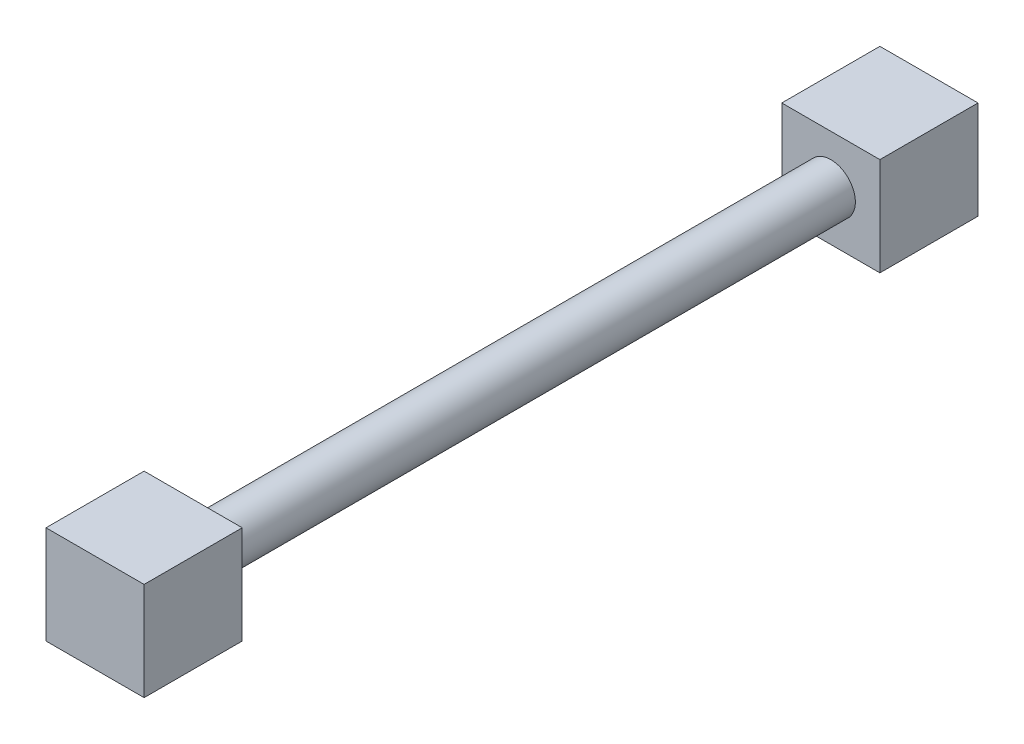
SolidWorks part; units mm, degrees
ref_plane "Front Plane" through (0, 0, 0) normal (0, 0, 1) x (1, 0, 0)
ref_plane "Top Plane" through (0, 0, 0) normal (0, 1, 0) x (1, 0, 0)
ref_plane "Right Plane" through (0, 0, 0) normal (1, 0, 0) x (0, 0, -1)
sketch "Sketch3" plane through (0, 0, 0) normal (0, 0, 1) x (1, 0, 0)
  circle A0 centre (0, 0) radius 12.7
  dimension "D1" = 25.4
extrude "Boss-Extrude1" add sketch "Sketch3" along normal blind 381
sketch "Sketch4" plane through (0, 0, 0) normal (0, 0, -1) x (-1, 0, 0)
  line L1 (-25.4, -25.4) -> (25.4, -25.4)
  line L2 (-25.4, -25.4) -> (-25.4, 25.4)
  line L3 (-25.4, 25.4) -> (25.4, 25.4)
  line L4 (25.4, -25.4) -> (25.4, 25.4)
  line L5 (-25.4, -25.4) -> (25.4, 25.4) construction
  line L6 (-25.4, 25.4) -> (25.4, -25.4) construction
  point P0 (0, 0)
  dimension "D1" = 50.8
  dimension "D2" = 50.8
extrude "Boss-Extrude2" add sketch "Sketch4" along normal mid plane 50.8
sketch "Sketch5" plane through (0, 0, 381) normal (0, 0, 1) x (1, 0, 0)
  line L1 (-25.4, -25.4) -> (25.4, -25.4)
  line L2 (-25.4, -25.4) -> (-25.4, 25.4)
  line L3 (-25.4, 25.4) -> (25.4, 25.4)
  line L4 (25.4, -25.4) -> (25.4, 25.4)
  line L5 (-25.4, -25.4) -> (25.4, 25.4) construction
  line L6 (-25.4, 25.4) -> (25.4, -25.4) construction
  point P0 (0, 0)
extrude "Boss-Extrude3" add sketch "Sketch5" along normal mid plane 50.8
